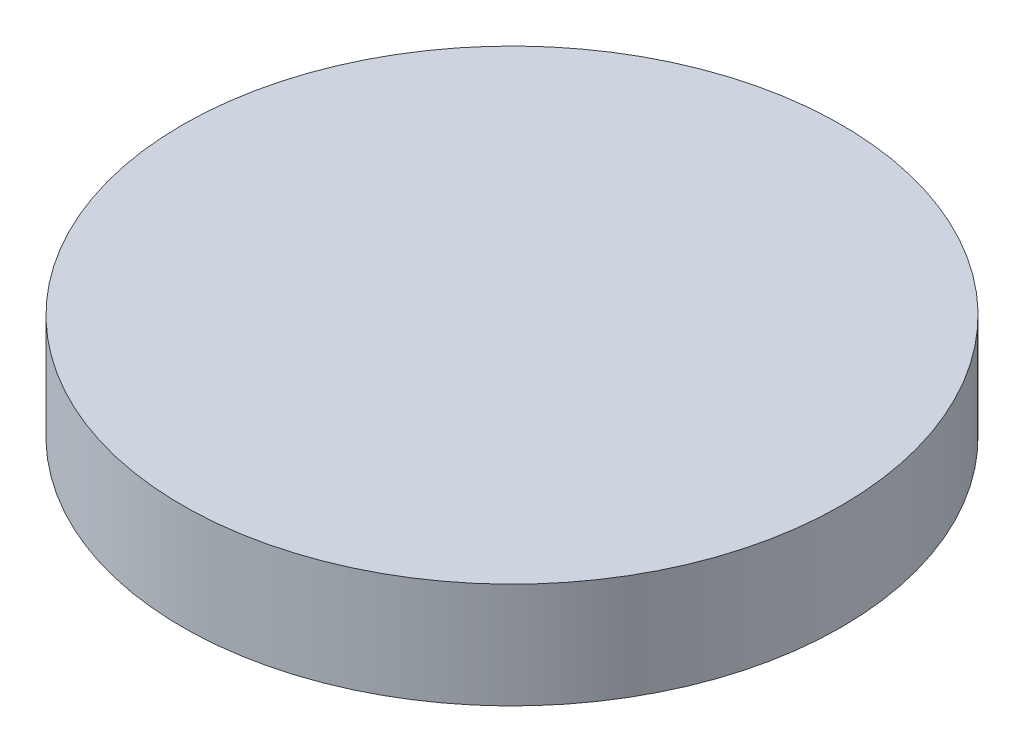
SolidWorks part; units mm, degrees
ref_plane "Front Plane" through (0, 0, 0) normal (0, 0, 1) x (1, 0, 0)
ref_plane "Top Plane" through (0, 0, 0) normal (0, 1, 0) x (1, 0, 0)
ref_plane "Right Plane" through (0, 0, 0) normal (1, 0, 0) x (0, 0, -1)
sketch "Sketch1" plane through (0, 0, 0) normal (0, 0, 1) x (1, 0, 0)
  line L1 (0, 0) -> (-12.5, 0)
  line L2 (0, 0) -> (0, -4)
  line L3 (0, -4) -> (-12.5, -4)
  line L4 (-12.5, 0) -> (-12.5, -4)
  dimension "D1" = 12.5
  dimension "D2" = 4
revolve "Revolve1" add sketch "Sketch1" angle 360 about L2
